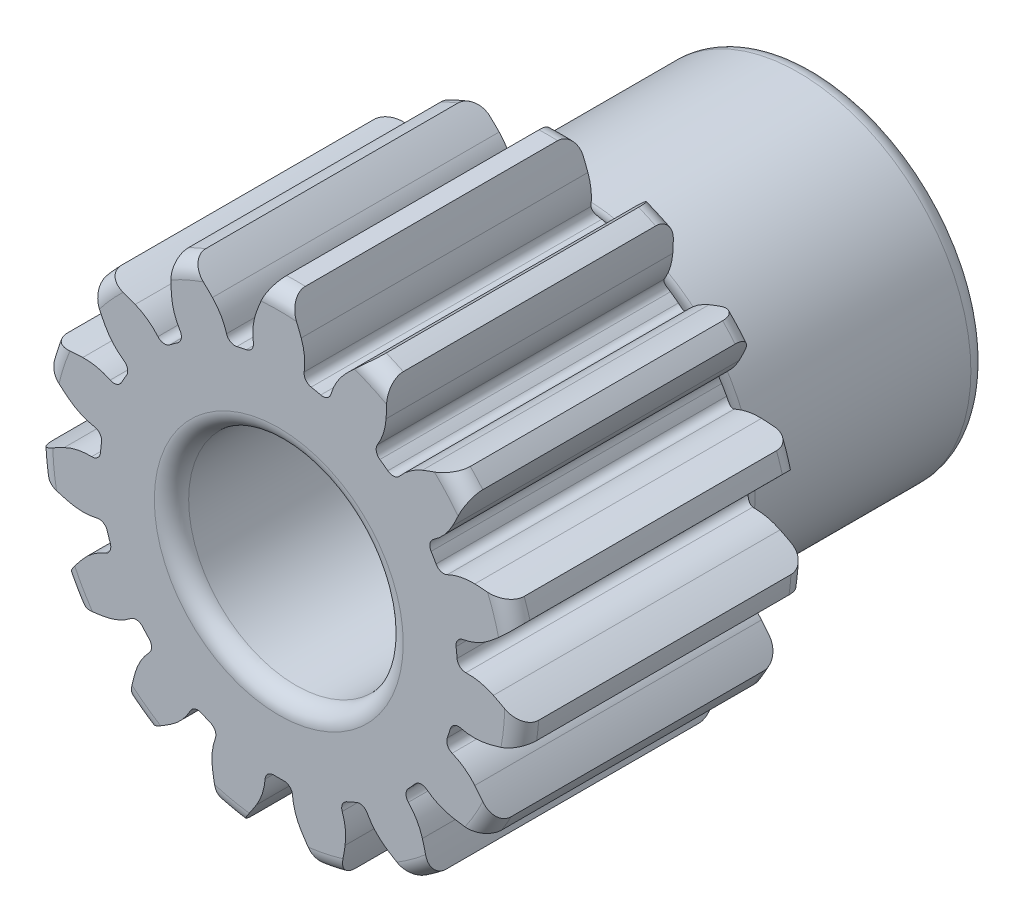
SolidWorks part; units mm, degrees
ref_plane "Front Plane" through (0, 0, 0) normal (0, 0, 1) x (1, 0, 0)
ref_plane "Top Plane" through (0, 0, 0) normal (0, 1, 0) x (1, 0, 0)
ref_plane "Right Plane" through (0, 0, 0) normal (1, 0, 0) x (0, 0, -1)
sketch "Sketch1" plane through (0, 0, 0) normal (0, 0, 1) x (1, 0, 0)
  line L0 (3.9208, 10.0709) -> (4.8607, 9.6525)
  line L1 (-10.795, 0) -> (10.795, 0) construction
  line L2 (0, 10.795) -> (0, 9.525) construction
  line L3 (0, 9.525) -> (0, 7.9375) construction
  line L4 (-0.5144, 10.795) -> (0.5144, 10.795)
  line L5 (-0.5144, 10.795) -> (-1.6149, 7.7715)
  line L6 (0.5144, 10.795) -> (1.6149, 7.7715)
  line L7 (3.9208, 10.0709) -> (1.6857, 7.7564)
  line L8 (-1.9949, -10.795) -> (1.9949, -10.795) construction
  line L9 (1.9949, -10.795) -> (0, -14.2503) construction
  line L10 (0, -14.2503) -> (-1.9949, -10.795) construction
  line L11 (0, -14.2503) -> (0, -14.1128) construction
  line L12 (-0.0794, -14.1128) -> (0.0794, -14.1128) construction
  line L13 (0, -10.9325) -> (0, -10.795) construction
  line L14 (4.3907, 9.8617) -> (0, 0) construction
  line L15 (1.9155, -10.9325) -> (-1.9155, -10.9325) construction
  line L16 (4.8607, 9.6525) -> (4.6362, 6.4428)
  line L17 (-1.9552, -10.8637) -> (1.9552, -10.8637) construction
  line L18 (0, 0) -> (-1.1281, 8.2328) construction
  line L19 (0, 0) -> (2.318, 7.9799) construction
  circle A0 centre (0, 0) radius 10.795
  circle A1 centre (0, 0) radius 9.525 construction
  circle A2 centre (0, 0) radius 4.7625
  circle A3 centre (0, 0) radius 7.9375
  arc A4 (-0.9956, 9.4728) -> (0.9956, 9.4728) centre (0, 0) cw
  circle A5 centre (0, 0) radius 7.6581 construction
  arc A6 (-1.4366, 7.8064) -> (-1.1281, 8.2328) centre (-1.5056, 8.1811) ccw
  circle A8 centre (0, 0) radius 8.255 construction
  arc A10 (-0.9956, 9.4728) -> (-1.1281, 8.2328) centre (1.4432, 8.5852) ccw
  arc A11 (-0.411, 10.795) -> (-0.9956, 9.4728) centre (9.1073, 5.7957) ccw
  arc A13 (1.8627, 7.7158) -> (2.318, 7.9799) centre (1.9521, 8.0862) ccw
  arc A15 (2.9434, 9.0588) -> (2.318, 7.9799) centre (4.8103, 7.256) ccw
  arc A16 (4.0153, 10.0289) -> (2.9434, 9.0588) centre (10.6772, 1.5903) ccw
  arc A17 (1.4366, 7.8064) -> (1.1281, 8.2328) centre (1.5056, 8.1811) cw
  arc A18 (0.9956, 9.4728) -> (1.1281, 8.2328) centre (-1.4432, 8.5852) cw
  arc A19 (0.411, 10.795) -> (0.9956, 9.4728) centre (-9.1073, 5.7957) cw
  arc A20 (4.4876, 6.5472) -> (4.3792, 7.0622) centre (4.703, 6.8614) cw
  arc A21 (4.7625, 8.2489) -> (4.3792, 7.0622) centre (2.1735, 8.4299) cw
  arc A22 (4.7662, 9.6946) -> (4.7625, 8.2489) centre (-5.9626, 8.9989) cw
  point P5 (0, 10.795)
  point P8 (4.3907, 9.8617)
  point P9 (8.0222, 7.2233)
  point P10 (10.2667, 3.3358)
  point P11 (10.7359, -1.1284)
  point P12 (9.3487, -5.3975)
  point P13 (6.3451, -8.7333)
  point P14 (2.2444, -10.5591)
  point P15 (-2.2444, -10.5591)
  point P16 (-6.3451, -8.7333)
  point P17 (-9.3487, -5.3975)
  point P18 (-10.7359, -1.1284)
  point P19 (-10.2667, 3.3358)
  point P20 (-8.0222, 7.2233)
  point P21 (-4.3907, 9.8617)
  point P22 (0, 0)
  point P37 (-1.9949, -10.795)
  point P47 (0, -10.8637)
  point P48 (61.8424, -10.795)
  point P49 (1.9949, -10.795)
  point P53 (5.9847, -10.795)
  point P54 (9.9746, -10.795)
  point P55 (13.9644, -10.795)
  point P56 (17.9542, -10.795)
  point P57 (21.9441, -10.795)
  point P58 (25.9339, -10.795)
  point P59 (29.9237, -10.795)
  point P60 (33.9136, -10.795)
  point P61 (37.9034, -10.795)
  point P62 (41.8932, -10.795)
  point P63 (45.8831, -10.795)
  point P64 (49.8729, -10.795)
  point P65 (53.8627, -10.795)
  point P66 (57.8526, -10.795)
  point P69 (65.8322, -10.795)
  point P70 (69.8221, -10.795)
  point P71 (73.8119, -10.795)
  point P81 (0, 7.6581)
  dimension "OD" = 21.59
  dimension "Shaft Diameter" = 9.525
  dimension "Pitch Diameter" = 19.05
  dimension "Hub Diameter" = 15.3162
  dimension "D4" = 0.381
  dimension "Driven Dim* Addendum (a)" = 1.27
  dimension "Dedendum (b)" = 1.5875
  dimension "D2" = 3.9898
  dimension "D3" = 0.1588
  dimension "Pressure Angle" = 20
  dimension "Clearance" = 0.3175
  dimension "D5" = 24
  dimension "D1" = 1.9949
  dimension "Gear Pitch" = 20
  dimension "Teeth" = 15
sketch "Sketch2" plane through (0, 0, 0) normal (1, 0, 0) x (0, 0, -1)
  line L0 (-11.9126, 10.033) -> (-11.9126, -10.033)
  line L1 (-11.1506, -10.795) -> (0.0508, -10.795)
  line L2 (0.8128, -10.033) -> (0.8128, -8.4201)
  line L3 (1.5748, -7.6581) -> (11.1506, -7.6581)
  line L4 (11.9126, -6.8961) -> (11.9126, 6.8961)
  line L5 (11.1506, 7.6581) -> (1.5748, 7.6581)
  line L6 (0.8128, 8.4201) -> (0.8128, 10.033)
  line L7 (0.0508, 10.795) -> (-11.1506, 10.795)
  line L8 (11.9126, 0) -> (-11.9126, 0) construction
  line L10 (0.8128, 7.6581) -> (-11.9126, 7.6581) construction
  line L13 (11.9126, 4.7625) -> (0, 4.7625) construction
  line L15 (-11.9126, 4.7625) -> (0, 4.7625) construction
  line L17 (11.9126, -4.7625) -> (0, -4.7625) construction
  line L18 (0, -4.7625) -> (-11.9126, -4.7625) construction
  arc A0 (-11.9126, -10.033) -> (-11.1506, -10.795) centre (-11.1506, -10.033) ccw
  arc A1 (0.0508, -10.795) -> (0.8128, -10.033) centre (0.0508, -10.033) ccw
  arc A2 (0.8128, -8.4201) -> (1.5748, -7.6581) centre (1.5748, -8.4201) cw
  arc A3 (11.9126, -6.8961) -> (11.1506, -7.6581) centre (11.1506, -6.8961) cw
  arc A4 (0.8128, 8.4201) -> (1.5748, 7.6581) centre (1.5748, 8.4201) ccw
  arc A5 (-11.9126, 10.033) -> (-11.1506, 10.795) centre (-11.1506, 10.033) cw
  arc A6 (0.0508, 10.795) -> (0.8128, 10.033) centre (0.0508, 10.033) cw
  arc A7 (11.1506, 7.6581) -> (11.9126, 6.8961) centre (11.1506, 6.8961) cw
  point P40 (11.9126, 7.6581)
  dimension "Radius" = 0.762
  dimension "Hub Width" = 11.0998
  dimension "Overall Width" = 23.8252
sketch "Sketch3" plane through (0, 0, 0) normal (1, 0, 0) x (0, 0, -1)
  line L0 (11.1506, 4.7625) -> (-11.1506, 4.7625)
  line L1 (11.9126, -6.8961) -> (11.9126, 6.8961) construction
  line L2 (11.1506, 7.6581) -> (1.5748, 7.6581) construction
  line L3 (0.8128, 8.4201) -> (0.8128, 10.033) construction
  line L4 (0.0508, 10.795) -> (-11.1506, 10.795) construction
  line L5 (-11.9126, 10.033) -> (-11.9126, -10.033) construction
  line L6 (11.9126, 5.5245) -> (11.9126, 6.8961)
  line L7 (11.1506, 7.6581) -> (1.5748, 7.6581)
  line L8 (0.8128, 8.4201) -> (0.8128, 10.033)
  line L9 (0.0508, 10.795) -> (-11.1506, 10.795)
  line L10 (-11.9126, 10.033) -> (-11.9126, 5.5245)
  line L11 (11.9126, 4.7625) -> (0, 4.7625) construction
  arc A8 (11.9126, 6.8961) -> (11.1506, 7.6581) centre (11.1506, 6.8961) ccw construction
  arc A9 (0.8128, 8.4201) -> (1.5748, 7.6581) centre (1.5748, 8.4201) ccw construction
  arc A10 (0.8128, 10.033) -> (0.0508, 10.795) centre (0.0508, 10.033) ccw construction
  arc A11 (-11.1506, 10.795) -> (-11.9126, 10.033) centre (-11.1506, 10.033) ccw construction
  arc A12 (11.9126, 6.8961) -> (11.1506, 7.6581) centre (11.1506, 6.8961) ccw
  arc A13 (0.8128, 8.4201) -> (1.5748, 7.6581) centre (1.5748, 8.4201) ccw
  arc A14 (0.8128, 10.033) -> (0.0508, 10.795) centre (0.0508, 10.033) ccw
  arc A15 (-11.1506, 10.795) -> (-11.9126, 10.033) centre (-11.1506, 10.033) ccw
  arc A16 (-11.9126, 5.5245) -> (-11.1506, 4.7625) centre (-11.1506, 5.5245) ccw
  arc A17 (11.1506, 4.7625) -> (11.9126, 5.5245) centre (11.1506, 5.5245) ccw
revolve "Revolve1" add sketch "Sketch3" angle 360 about L8
sketch "Sketch4" plane through (0, 0, 11.9126) normal (0, 0, 1) x (1, 0, 0)
  circle A9 centre (0, 0) radius 10.795 construction
  circle A21 centre (0, 0) radius 7.9375 construction
  arc A22 (1.8627, 7.7158) -> (2.318, 7.9799) centre (1.9521, 8.0862) ccw construction
  arc A23 (2.9434, 9.0588) -> (2.318, 7.9799) centre (4.8103, 7.256) ccw construction
  arc A24 (4.0153, 10.0289) -> (2.9434, 9.0588) centre (10.6772, 1.5903) ccw construction
  arc A25 (0.9956, 9.4728) -> (0.411, 10.795) centre (-9.1073, 5.7957) ccw construction
  arc A26 (1.1281, 8.2328) -> (0.9956, 9.4728) centre (-1.4432, 8.5852) ccw construction
  arc A27 (1.1281, 8.2328) -> (1.4366, 7.8064) centre (1.5056, 8.1811) ccw construction
  arc A28 (4.0082, 10.0233) -> (0.4152, 10.787) centre (0, 0) ccw
  arc A29 (1.8627, 7.7158) -> (1.4366, 7.8064) centre (0, 0) ccw
  arc A30 (1.8627, 7.7158) -> (2.318, 7.9799) centre (1.9521, 8.0862) ccw
  arc A31 (2.9434, 9.0588) -> (2.318, 7.9799) centre (4.8103, 7.256) ccw
  arc A32 (4.0082, 10.0233) -> (2.9434, 9.0588) centre (10.6772, 1.5903) ccw
  arc A33 (0.9956, 9.4728) -> (0.4152, 10.787) centre (-9.1073, 5.7957) ccw
  arc A34 (1.1281, 8.2328) -> (0.9956, 9.4728) centre (-1.4432, 8.5852) ccw
  arc A35 (1.1281, 8.2328) -> (1.4366, 7.8064) centre (1.5056, 8.1811) ccw
extrude "Cut-Extrude1" cut sketch "Sketch4" against normal through all both and the other way through all
pattern_circular "CirPattern1" count 15 every 24 about axis through (0, 0, 0) along (0, 0, 1) of "Cut-Extrude1"
equation "\"D3@Sketch1\"=(1/\"Gear Pitch@Sketch1\")/8"
equation "\"D2@Sketch1\"=3.1416/\"Gear Pitch@Sketch1\""
equation "\"Dedendum (b)@Sketch1\"=1.25/\"Gear Pitch@Sketch1\""
equation "\"D1@Sketch1\"=1.5708/\"Gear Pitch@Sketch1\""
equation "\"D4@Sketch1\"=.3/\"Gear Pitch@Sketch1\""
equation "\"Clearance@Sketch1\" = .25 / \"Gear Pitch@Sketch1\""
equation "\"D1@CirPattern1\"=\"Teeth@Sketch1\""
equation "\"D5@Sketch1\"=360/\"Teeth@Sketch1\""
equation "\"D2@CirPattern1\"=\"D5@Sketch1\""
equation "\"Radius@Sketch2\"=.6/\"Gear Pitch@Sketch1\""
